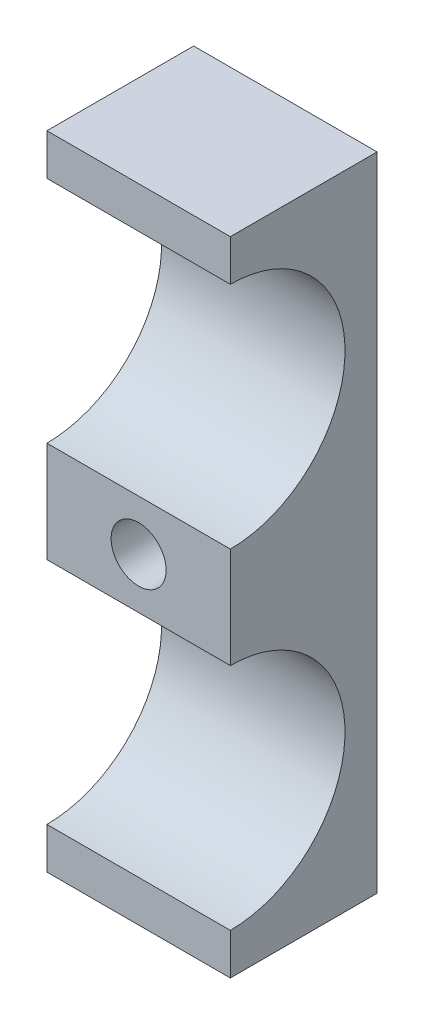
SolidWorks part; units mm, degrees
ref_plane "Płaszczyzna przednia" through (0, 0, 0) normal (0, 0, 1) x (1, 0, 0)
ref_plane "Płaszczyzna górna" through (0, 0, 0) normal (0, 1, 0) x (1, 0, 0)
ref_plane "Płaszczyzna prawa" through (0, 0, 0) normal (1, 0, 0) x (0, 0, -1)
sketch "Szkic1" plane through (0, 0, 0) normal (0, 0, 1) x (1, 0, 0)
  line L1 (-10, -35) -> (10, -35)
  line L2 (-10, -35) -> (-10, 35)
  line L3 (-10, 35) -> (10, 35)
  line L4 (10, -35) -> (10, 35)
  line L5 (-10, -35) -> (10, 35) construction
  line L6 (-10, 35) -> (10, -35) construction
  point P0 (0, 0)
  dimension "D1" = 70
  dimension "D2" = 20
extrude "Dodanie-wyciągnięcie1" add sketch "Szkic1" along normal blind 16
sketch "Szkic2" plane through (-10, 0, 0) normal (-1, 0, 0) x (0, 0, 1)
  line L0 (16, 35) -> (16, -35) construction
  line L1 (0, 0) -> (16, 0) construction
  line L2 (0, 35) -> (0, -35) construction
  circle A0 centre (16, 18) radius 12.5
  circle A1 centre (16, -18) radius 12.5
  dimension "D1" = 18
  dimension "D2" = 25
extrude "Wytnij-wyciągnięcie1" cut sketch "Szkic2" against normal through all
sketch "Szkic3" plane through (0, 0, 16) normal (0, 0, 1) x (1, 0, 0)
  circle A0 centre (0, 0) radius 3
  dimension "D1" = 6
extrude "Wytnij-wyciągnięcie2" cut sketch "Szkic3" against normal through all
